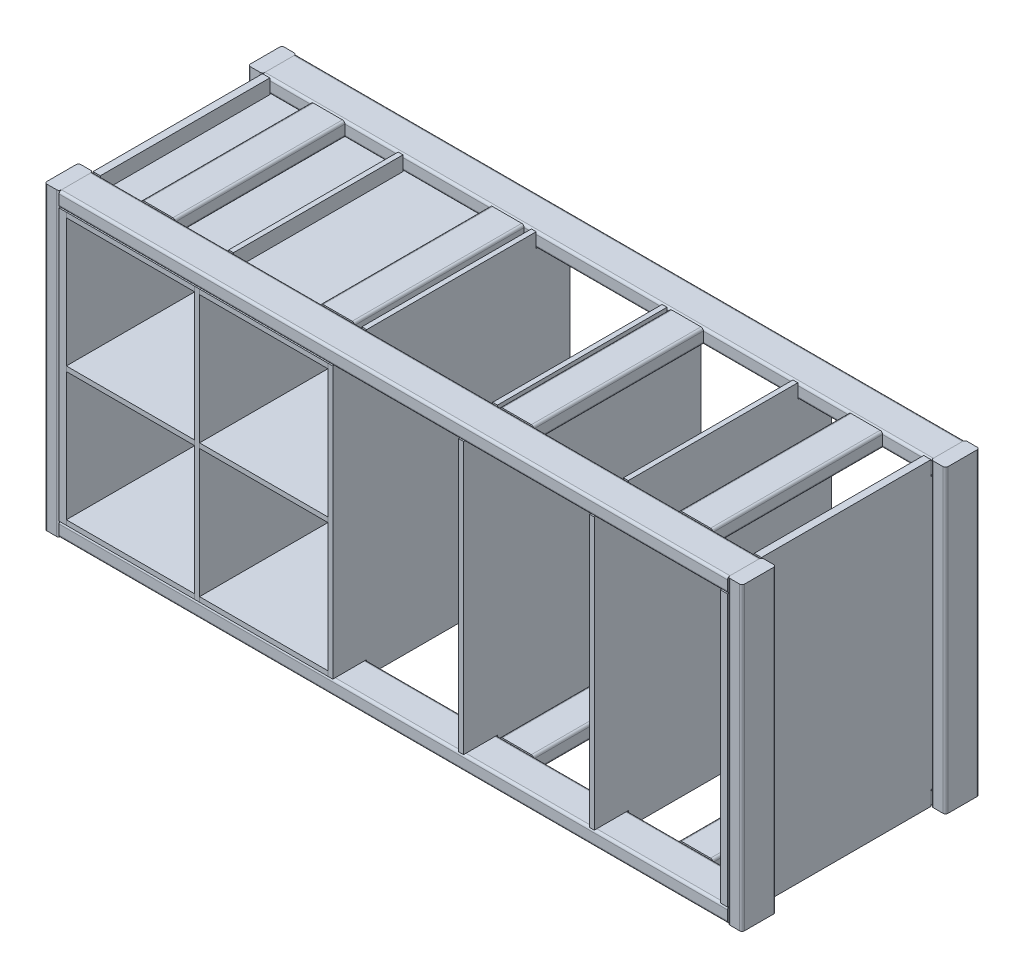
SolidWorks part; units mm, degrees
material "Pine"
ref_plane "Front Plane" through (0, 0, 0) normal (0, 0, 1) x (1, 0, 0)
ref_plane "Top Plane" through (0, 0, 0) normal (0, 1, 0) x (1, 0, 0)
ref_plane "Right Plane" through (0, 0, 0) normal (1, 0, 0) x (0, 0, -1)
sketch "Sketch2" plane through (0, 0, 0) normal (0, 1, 0) x (1, 0, 0)
  line L1 (0, 0) -> (1841.5, 0) construction
  line L2 (0, 0) -> (0, -622.3) construction
  line L3 (0, -622.3) -> (1841.5, -622.3) construction
  line L4 (1841.5, 0) -> (1841.5, -622.3) construction
  line L5 (12.7, 0) -> (38.1, 0)
  line L6 (6.35, -6.35) -> (6.35, -82.55)
  line L7 (12.7, -88.9) -> (38.1, -88.9)
  line L8 (44.45, -6.35) -> (44.45, -82.55)
  line L9 (12.7, -533.4) -> (38.1, -533.4)
  line L10 (6.35, -539.75) -> (6.35, -615.95)
  line L11 (12.7, -622.3) -> (38.1, -622.3)
  line L12 (44.45, -539.75) -> (44.45, -615.95)
  line L13 (1803.4, -622.3) -> (1828.8, -622.3)
  line L14 (1797.05, -615.95) -> (1797.05, -539.75)
  line L15 (1803.4, -533.4) -> (1828.8, -533.4)
  line L16 (1835.15, -615.95) -> (1835.15, -539.75)
  line L17 (1828.8, -88.9) -> (1803.4, -88.9)
  line L18 (1835.15, -82.55) -> (1835.15, -6.35)
  line L19 (1828.8, 0) -> (1803.4, 0)
  line L20 (1797.05, -82.55) -> (1797.05, -6.35)
  arc A0 (12.7, -533.4) -> (6.35, -539.75) centre (12.7, -539.75) ccw
  arc A1 (38.1, -533.4) -> (44.45, -539.75) centre (38.1, -539.75) cw
  arc A2 (38.1, -622.3) -> (44.45, -615.95) centre (38.1, -615.95) ccw
  arc A3 (6.35, -615.95) -> (12.7, -622.3) centre (12.7, -615.95) ccw
  arc A4 (12.7, 0) -> (6.35, -6.35) centre (12.7, -6.35) ccw
  arc A5 (38.1, 0) -> (44.45, -6.35) centre (38.1, -6.35) cw
  arc A6 (38.1, -88.9) -> (44.45, -82.55) centre (38.1, -82.55) ccw
  arc A7 (6.35, -82.55) -> (12.7, -88.9) centre (12.7, -82.55) ccw
  arc A8 (1803.4, 0) -> (1797.05, -6.35) centre (1803.4, -6.35) ccw
  arc A9 (1835.15, -6.35) -> (1828.8, 0) centre (1828.8, -6.35) ccw
  arc A10 (1828.8, -88.9) -> (1835.15, -82.55) centre (1828.8, -82.55) ccw
  arc A11 (1803.4, -88.9) -> (1797.05, -82.55) centre (1803.4, -82.55) cw
  arc A12 (1797.05, -539.75) -> (1803.4, -533.4) centre (1803.4, -539.75) cw
  arc A13 (1828.8, -533.4) -> (1835.15, -539.75) centre (1828.8, -539.75) cw
  arc A14 (1828.8, -622.3) -> (1835.15, -615.95) centre (1828.8, -615.95) ccw
  arc A15 (1803.4, -622.3) -> (1797.05, -615.95) centre (1803.4, -615.95) cw
  point P49 (1835.15, -533.4)
  point P52 (1835.15, -622.3)
  point P55 (1797.05, -622.3)
  dimension "D7" = 6.35
  dimension "D1" = 1841.5
  dimension "D2" = 622.3
  dimension "D3" = 88.9
  dimension "D4" = 38.1
  dimension "D5" = 6.35
  dimension "D6" = 6.35
extrude "Boss-Extrude1" add sketch "Sketch2" along normal blind 787.4
sketch "Sketch3" plane through (44.45, 0, 0) normal (1, 0, 0) x (0, 0, -1)
  line L0 (-622.3, 787.4) -> (-622.3, 0) construction
  line L1 (-615.95, 0) -> (-539.75, 0)
  line L2 (-622.3, 6.35) -> (-622.3, 31.75)
  line L3 (-615.95, 38.1) -> (-539.75, 38.1)
  line L4 (-533.4, 6.35) -> (-533.4, 31.75)
  line L5 (-82.55, 0) -> (-6.35, 0)
  line L6 (-88.9, 6.35) -> (-88.9, 31.75)
  line L7 (-82.55, 38.1) -> (-6.35, 38.1)
  line L8 (0, 6.35) -> (0, 31.75)
  line L9 (-6.35, 787.4) -> (-82.55, 787.4)
  line L10 (0, 781.05) -> (0, 755.65)
  line L11 (-6.35, 749.3) -> (-82.55, 749.3)
  line L12 (-88.9, 781.05) -> (-88.9, 755.65)
  line L13 (-539.75, 749.3) -> (-615.95, 749.3)
  line L14 (-533.4, 755.65) -> (-533.4, 781.05)
  line L15 (-539.75, 787.4) -> (-615.95, 787.4)
  line L16 (-622.3, 755.65) -> (-622.3, 781.05)
  line L17 (-615.95, 0) -> (-539.75, 0) construction
  line L18 (0, 787.4) -> (0, 0) construction
  line L19 (-615.95, 787.4) -> (-539.75, 787.4) construction
  arc A0 (-533.4, 781.05) -> (-539.75, 787.4) centre (-539.75, 781.05) ccw
  arc A1 (-539.75, 749.3) -> (-533.4, 755.65) centre (-539.75, 755.65) ccw
  arc A2 (-615.95, 749.3) -> (-622.3, 755.65) centre (-615.95, 755.65) cw
  arc A3 (-615.95, 787.4) -> (-622.3, 781.05) centre (-615.95, 781.05) ccw
  arc A4 (-6.35, 787.4) -> (0, 781.05) centre (-6.35, 781.05) cw
  arc A5 (0, 755.65) -> (-6.35, 749.3) centre (-6.35, 755.65) cw
  arc A6 (-82.55, 749.3) -> (-88.9, 755.65) centre (-82.55, 755.65) cw
  arc A7 (-82.55, 787.4) -> (-88.9, 781.05) centre (-82.55, 781.05) ccw
  arc A8 (-6.35, 38.1) -> (0, 31.75) centre (-6.35, 31.75) cw
  arc A9 (-6.35, 0) -> (0, 6.35) centre (-6.35, 6.35) ccw
  arc A10 (-82.55, 0) -> (-88.9, 6.35) centre (-82.55, 6.35) cw
  arc A11 (-88.9, 31.75) -> (-82.55, 38.1) centre (-82.55, 31.75) cw
  arc A12 (-539.75, 38.1) -> (-533.4, 31.75) centre (-539.75, 31.75) cw
  arc A13 (-539.75, 0) -> (-533.4, 6.35) centre (-539.75, 6.35) ccw
  arc A14 (-615.95, 0) -> (-622.3, 6.35) centre (-615.95, 6.35) cw
  arc A15 (-622.3, 31.75) -> (-615.95, 38.1) centre (-615.95, 31.75) cw
  point P52 (-533.4, 0)
  point P55 (-622.3, 0)
  point P58 (-622.3, 38.1)
  dimension "D3" = 6.35
  dimension "D1" = 88.9
  dimension "D2" = 38.1
extrude "Boss-Extrude2" add sketch "Sketch3" along normal up to surface (1752.6 mm away) separate body up to face at (1797.05, 393.7, 577.85)
sketch "Sketch8" plane through (1797.05, 0, 0) normal (-1, 0, 0) x (0, 0, 1)
  line L0 (622.3, 38.1) -> (622.3, 749.3)
  line L1 (622.3, 749.3) -> (533.4, 749.3)
  line L2 (533.4, 749.3) -> (533.4, 787.4)
  line L3 (533.4, 787.4) -> (88.9, 787.4)
  line L4 (88.9, 787.4) -> (88.9, 749.3)
  line L5 (88.9, 749.3) -> (0, 749.3)
  line L6 (0, 749.3) -> (0, 38.1)
  line L7 (0, 38.1) -> (88.9, 38.1)
  line L8 (88.9, 38.1) -> (88.9, 0)
  line L9 (88.9, 0) -> (533.4, 0)
  line L10 (533.4, 0) -> (533.4, 38.1)
  line L11 (533.4, 38.1) -> (622.3, 38.1)
  line L13 (88.9, 787.4) -> (88.9, 0) construction
  line L14 (0, 787.4) -> (0, 0) construction
  line L15 (533.4, 787.4) -> (533.4, 0) construction
  line L17 (539.75, 787.4) -> (615.95, 787.4) construction
  line L18 (539.75, 0) -> (615.95, 0) construction
  line L19 (6.35, 38.1) -> (82.55, 38.1) construction
  line L20 (539.75, 38.1) -> (615.95, 38.1) construction
  line L21 (82.55, 749.3) -> (6.35, 749.3) construction
  line L22 (615.95, 749.3) -> (539.75, 749.3) construction
  line L24 (622.3, 787.4) -> (622.3, 0) construction
extrude "Boss-Extrude5" add sketch "Sketch8" along normal blind 19.05 separate body
ref_plane "Plane2" through (920.75, 0, 0) normal (1, 0, 0) x (0, 0, -1)
mirror "Mirror1" about plane through (920.75, 0, 0) normal (1, 0, 0) of bodies 123
ref_plane "Plane3" through (1447.8, 0, 0) normal (-1, 0, 0) x (0, 0, 1)
sketch "Sketch12" plane through (1447.8, 0, 0) normal (-1, 0, 0) x (0, 0, 1)
  line L12 (622.3, 38.1) -> (622.3, 749.3)
  line L13 (622.3, 749.3) -> (533.4, 749.3)
  line L14 (533.4, 749.3) -> (533.4, 787.4)
  line L15 (533.4, 787.4) -> (88.9, 787.4)
  line L16 (88.9, 787.4) -> (88.9, 749.3)
  line L17 (88.9, 749.3) -> (0, 749.3)
  line L18 (0, 749.3) -> (0, 38.1)
  line L19 (0, 38.1) -> (88.9, 38.1)
  line L20 (88.9, 38.1) -> (88.9, 0)
  line L21 (88.9, 0) -> (533.4, 0)
  line L22 (533.4, 0) -> (533.4, 38.1)
  line L23 (533.4, 38.1) -> (622.3, 38.1)
  line L24 (622.3, 38.1) -> (622.3, 749.3)
  line L25 (622.3, 749.3) -> (533.4, 749.3)
  line L26 (533.4, 749.3) -> (533.4, 787.4)
  line L27 (533.4, 787.4) -> (88.9, 787.4)
  line L28 (88.9, 787.4) -> (88.9, 749.3)
  line L29 (88.9, 749.3) -> (0, 749.3)
  line L30 (0, 749.3) -> (0, 38.1)
  line L31 (0, 38.1) -> (88.9, 38.1)
  line L32 (88.9, 38.1) -> (88.9, 0)
  line L33 (88.9, 0) -> (533.4, 0)
  line L34 (533.4, 0) -> (533.4, 38.1)
  line L35 (533.4, 38.1) -> (622.3, 38.1)
  dimension "D1" = 0
extrude "Boss-Extrude7" add sketch "Sketch12" along normal blind 12.7 separate body
pattern_linear "LPattern1" count 3 spacing 342.9 along (-1, 0, 0) of bodies 136 123
ref_plane "Plane1" through (1612.9, 0, 0) normal (-1, 0, 0) x (0, 0, 1)
sketch "Sketch4" plane through (0, 0, 88.9) normal (0, 0, 1) x (1, 0, 0)
  line L0 (1797.05, 0) -> (44.45, 0) construction
  line L1 (647.7, 38.1) -> (723.9, 38.1)
  line L2 (641.35, 31.75) -> (641.35, 6.35)
  line L3 (647.7, 0) -> (723.9, 0)
  line L4 (730.25, 31.75) -> (730.25, 6.35)
  line L5 (1117.6, 38.1) -> (1193.8, 38.1)
  line L6 (1111.25, 31.75) -> (1111.25, 6.35)
  line L7 (1117.6, 0) -> (1193.8, 0)
  line L8 (1200.15, 31.75) -> (1200.15, 6.35)
  line L9 (1193.8, 749.3) -> (1117.6, 749.3)
  line L10 (1200.15, 755.65) -> (1200.15, 781.05)
  line L11 (1193.8, 787.4) -> (1117.6, 787.4)
  line L12 (1111.25, 755.65) -> (1111.25, 781.05)
  line L13 (723.9, 787.4) -> (647.7, 787.4)
  line L14 (730.25, 781.05) -> (730.25, 755.65)
  line L15 (723.9, 749.3) -> (647.7, 749.3)
  line L16 (641.35, 781.05) -> (641.35, 755.65)
  line L17 (1797.05, 787.4) -> (44.45, 787.4) construction
  line L18 (730.25, 19.05) -> (1111.25, 19.05) construction
  line L19 (1797.05, 0) -> (44.45, 0) construction
  arc A0 (1200.15, 781.05) -> (1193.8, 787.4) centre (1193.8, 781.05) ccw
  arc A1 (1193.8, 749.3) -> (1200.15, 755.65) centre (1193.8, 755.65) ccw
  arc A2 (1117.6, 749.3) -> (1111.25, 755.65) centre (1117.6, 755.65) cw
  arc A3 (1117.6, 787.4) -> (1111.25, 781.05) centre (1117.6, 781.05) ccw
  arc A4 (1193.8, 38.1) -> (1200.15, 31.75) centre (1193.8, 31.75) cw
  arc A5 (1193.8, 0) -> (1200.15, 6.35) centre (1193.8, 6.35) ccw
  arc A6 (1111.25, 6.35) -> (1117.6, 0) centre (1117.6, 6.35) ccw
  arc A7 (1117.6, 38.1) -> (1111.25, 31.75) centre (1117.6, 31.75) ccw
  arc A8 (723.9, 38.1) -> (730.25, 31.75) centre (723.9, 31.75) cw
  arc A9 (723.9, 0) -> (730.25, 6.35) centre (723.9, 6.35) ccw
  arc A10 (641.35, 6.35) -> (647.7, 0) centre (647.7, 6.35) ccw
  arc A11 (647.7, 38.1) -> (641.35, 31.75) centre (647.7, 31.75) ccw
  arc A12 (723.9, 787.4) -> (730.25, 781.05) centre (723.9, 781.05) cw
  arc A13 (730.25, 755.65) -> (723.9, 749.3) centre (723.9, 755.65) cw
  arc A14 (647.7, 749.3) -> (641.35, 755.65) centre (647.7, 755.65) cw
  arc A15 (647.7, 787.4) -> (641.35, 781.05) centre (647.7, 781.05) ccw
  point P22 (920.75, 19.05)
  point P25 (920.75, 0)
  point P36 (1200.15, 38.1)
  point P39 (1200.15, 0)
  point P42 (1111.25, 0)
  dimension "D4" = 6.35
  dimension "D1" = 381
  dimension "D2" = 88.9
  dimension "D3" = 38.1
extrude "Boss-Extrude3" add sketch "Sketch4" along normal up to surface (444.5 mm away) separate body up to face at (920.75, 19.05, 533.4)
sketch "Sketch10" plane through (0, 0, 88.9) normal (0, 0, 1) x (1, 0, 0)
  line L0 (1797.05, 0) -> (44.45, 0) construction
  line L1 (177.8, 38.1) -> (254, 38.1)
  line L2 (171.45, 31.75) -> (171.45, 6.35)
  line L3 (177.8, 0) -> (254, 0)
  line L4 (260.35, 31.75) -> (260.35, 6.35)
  line L5 (1587.5, 38.1) -> (1663.7, 38.1)
  line L6 (1581.15, 31.75) -> (1581.15, 6.35)
  line L7 (1587.5, 0) -> (1663.7, 0)
  line L8 (1670.05, 31.75) -> (1670.05, 6.35)
  line L9 (1663.7, 749.3) -> (1587.5, 749.3)
  line L10 (1670.05, 755.65) -> (1670.05, 781.05)
  line L11 (1663.7, 787.4) -> (1587.5, 787.4)
  line L12 (1581.15, 755.65) -> (1581.15, 781.05)
  line L13 (254, 787.4) -> (177.8, 787.4)
  line L14 (260.35, 781.05) -> (260.35, 755.65)
  line L15 (254, 749.3) -> (177.8, 749.3)
  line L16 (171.45, 781.05) -> (171.45, 755.65)
  line L17 (1797.05, 787.4) -> (44.45, 787.4) construction
  line L19 (1797.05, 31.75) -> (1797.05, 6.35) construction
  line L21 (44.45, 31.75) -> (44.45, 6.35) construction
  arc A0 (1663.7, 38.1) -> (1670.05, 31.75) centre (1663.7, 31.75) cw
  arc A1 (1663.7, 0) -> (1670.05, 6.35) centre (1663.7, 6.35) ccw
  arc A2 (1581.15, 6.35) -> (1587.5, 0) centre (1587.5, 6.35) ccw
  arc A3 (1587.5, 38.1) -> (1581.15, 31.75) centre (1587.5, 31.75) ccw
  arc A4 (254, 38.1) -> (260.35, 31.75) centre (254, 31.75) cw
  arc A5 (254, 0) -> (260.35, 6.35) centre (254, 6.35) ccw
  arc A6 (171.45, 6.35) -> (177.8, 0) centre (177.8, 6.35) ccw
  arc A7 (177.8, 38.1) -> (171.45, 31.75) centre (177.8, 31.75) ccw
  arc A8 (254, 787.4) -> (260.35, 781.05) centre (254, 781.05) cw
  arc A9 (260.35, 755.65) -> (254, 749.3) centre (254, 755.65) cw
  arc A10 (177.8, 749.3) -> (171.45, 755.65) centre (177.8, 755.65) cw
  arc A11 (177.8, 787.4) -> (171.45, 781.05) centre (177.8, 781.05) ccw
  arc A12 (1670.05, 781.05) -> (1663.7, 787.4) centre (1663.7, 781.05) ccw
  arc A13 (1663.7, 749.3) -> (1670.05, 755.65) centre (1663.7, 755.65) ccw
  arc A14 (1587.5, 749.3) -> (1581.15, 755.65) centre (1587.5, 755.65) cw
  arc A15 (1587.5, 787.4) -> (1581.15, 781.05) centre (1587.5, 781.05) ccw
  point P26 (1670.05, 38.1)
  point P29 (1670.05, 0)
  point P32 (1581.15, 0)
  dimension "D5" = 6.35
  dimension "D1" = 88.9
  dimension "D2" = 38.1
  dimension "D3" = 127
  dimension "D4" = 127
extrude "Boss-Extrude6" add sketch "Sketch10" along normal up to surface (444.5 mm away) separate body up to face at (920.75, 19.05, 533.4)
ref_plane "Plane4" through (406.4, 0, 0) normal (-1, 0, 0) x (0, 0, 1)
sketch "Sketch13" plane through (406.4, 0, 0) normal (-1, 0, 0) x (0, 0, 1)
  line L0 (12.7, 749.3) -> (12.7, 38.1)
  line L1 (12.7, 749.3) -> (0, 749.3) construction
  line L2 (0, 38.1) -> (12.7, 38.1) construction
  line L12 (622.3, 38.1) -> (622.3, 749.3)
  line L13 (622.3, 749.3) -> (533.4, 749.3)
  line L14 (533.4, 749.3) -> (533.4, 787.4)
  line L15 (533.4, 787.4) -> (88.9, 787.4)
  line L16 (88.9, 787.4) -> (88.9, 749.3)
  line L17 (88.9, 749.3) -> (0, 749.3)
  line L18 (0, 749.3) -> (0, 38.1)
  line L19 (0, 38.1) -> (88.9, 38.1)
  line L20 (88.9, 38.1) -> (88.9, 0)
  line L21 (88.9, 0) -> (533.4, 0)
  line L22 (533.4, 0) -> (533.4, 38.1)
  line L23 (533.4, 38.1) -> (622.3, 38.1)
  line L24 (622.3, 38.1) -> (622.3, 749.3)
  line L25 (622.3, 749.3) -> (533.4, 749.3)
  line L26 (533.4, 749.3) -> (533.4, 787.4)
  line L27 (533.4, 787.4) -> (88.9, 787.4)
  line L28 (88.9, 787.4) -> (88.9, 749.3)
  line L29 (88.9, 749.3) -> (12.7, 749.3)
  line L30 (0, 749.3) -> (0, 38.1) construction
  line L31 (12.7, 38.1) -> (88.9, 38.1)
  line L32 (88.9, 38.1) -> (88.9, 0)
  line L33 (88.9, 0) -> (533.4, 0)
  line L34 (533.4, 0) -> (533.4, 38.1)
  line L35 (533.4, 38.1) -> (622.3, 38.1)
  dimension "D2" = 12.7
  dimension "D1" = 0
extrude "Boss-Extrude8" add sketch "Sketch13" along normal mid plane 12.7 separate body
sketch "Sketch14" plane through (0, 0, 0) normal (0, 0, -1) x (-1, 0, 0)
  line L0 (-749.3, 749.3) -> (-749.3, 38.1) construction
  line L1 (-749.3, 749.3) -> (-63.5, 749.3)
  line L2 (-749.3, 749.3) -> (-749.3, 38.1)
  line L3 (-749.3, 38.1) -> (-63.5, 38.1)
  line L4 (-63.5, 749.3) -> (-63.5, 38.1)
  line L5 (-63.5, 749.3) -> (-63.5, 38.1) construction
  line L6 (-1797.05, 749.3) -> (-44.45, 749.3) construction
  line L7 (-1797.05, 38.1) -> (-44.45, 38.1) construction
extrude "Boss-Extrude9" add sketch "Sketch14" against normal up to surface (12.7 mm away) separate body up to face at (406.4, 393.7, 12.7)
sketch "Sketch15" plane through (0, 38.1, 0) normal (0, 1, 0) x (1, 0, 0)
  line L0 (749.3, -533.4) -> (749.3, -622.3) construction
  line L1 (63.5, -622.3) -> (400.05, -622.3)
  line L2 (63.5, -622.3) -> (63.5, -12.7)
  line L3 (63.5, -12.7) -> (400.05, -12.7)
  line L4 (400.05, -622.3) -> (400.05, -12.7)
  line L5 (412.75, -12.7) -> (749.3, -12.7)
  line L6 (412.75, -12.7) -> (412.75, -622.3)
  line L7 (412.75, -622.3) -> (749.3, -622.3)
  line L8 (749.3, -12.7) -> (749.3, -622.3)
  line L9 (400.05, -533.4) -> (400.05, -622.3) construction
  line L10 (63.5, -533.4) -> (63.5, -622.3) construction
  line L11 (412.75, -533.4) -> (412.75, -622.3) construction
  line L12 (1797.05, -622.3) -> (44.45, -622.3) construction
  line L13 (749.3, -12.7) -> (63.5, -12.7) construction
extrude "Boss-Extrude10" add sketch "Sketch15" along normal blind 12.7 separate body
pattern_linear "LPattern3" count 3 spacing 349.25 along (0, 1, 0) of bodies 142 141
